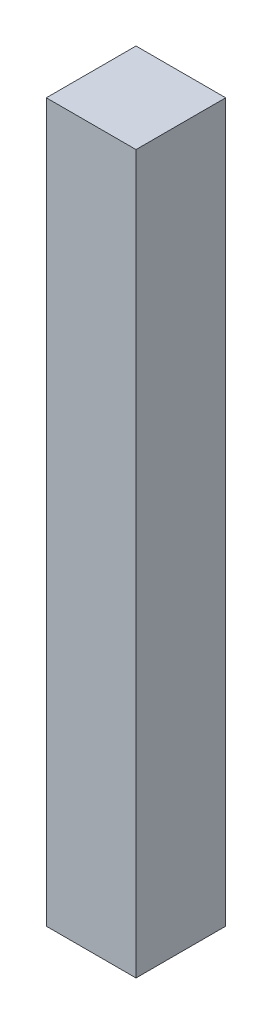
SolidWorks part; units mm, degrees
ref_plane "前视基准面" through (0, 0, 0) normal (0, 0, 1) x (1, 0, 0)
ref_plane "上视基准面" through (0, 0, 0) normal (0, 1, 0) x (1, 0, 0)
ref_plane "右视基准面" through (0, 0, 0) normal (1, 0, 0) x (0, 0, -1)
other "Configuration Table"
sketch "草图1" plane through (0, 0, 0) normal (0, 0, 1) x (1, 0, 0)
  line L9 (-85.6925, 51.9886) -> (-53.8425, 51.9886)
  line L10 (-85.6925, 51.9886) -> (-85.6925, 26.7886)
  line L11 (-85.6925, 26.7886) -> (-53.8425, 26.7886)
  line L12 (-53.8425, 51.9886) -> (-53.8425, 26.7886)
  line L13 (-56.3425, 49.3886) -> (-53.8425, 49.3886)
  line L14 (-56.3425, 49.3886) -> (-56.3425, 29.3886)
  line L15 (-56.3425, 29.3886) -> (-53.8425, 29.3886)
  line L16 (-53.8425, 49.3886) -> (-53.8425, 29.3886)
  line L17 (-85.6925, 46.3886) -> (-70.6925, 46.3886)
  line L18 (-85.6925, 46.3886) -> (-85.6925, 32.3886)
  line L19 (-85.6925, 32.3886) -> (-70.6925, 32.3886)
  line L20 (-70.6925, 46.3886) -> (-70.6925, 32.3886)
  dimension "D1" = 31.85
  dimension "D2" = 25.2
  dimension "D3" = 2.5
  dimension "D4" = 20
  dimension "D5" = 2.6
  dimension "D6" = 0
  dimension "D7" = 2.6
  dimension "D8" = 5.6
  dimension "D9" = 14
  dimension "D10" = 15
  dimension "D11" = 5.6
extrude "凸台-拉伸5" add sketch "草图1" along normal blind 2.5 contours L14 L15 L16 L13
